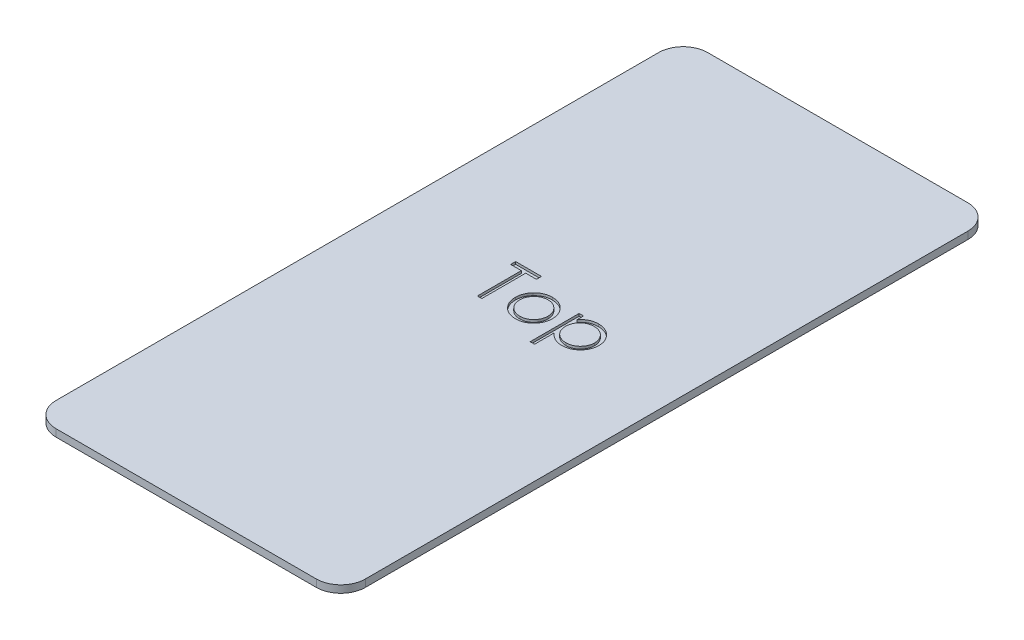
SolidWorks part; units mm, degrees
ref_plane "Front Plane" through (0, 0, 0) normal (0, 0, 1) x (1, 0, 0)
ref_plane "Top Plane" through (0, 0, 0) normal (0, 1, 0) x (1, 0, 0)
ref_plane "Right Plane" through (0, 0, 0) normal (1, 0, 0) x (0, 0, -1)
sketch "Sketch1" plane through (0, 0, 0) normal (0, 1, 0) x (1, 0, 0)
  line L1 (-63.105, -132.955) -> (63.105, -132.955)
  line L2 (-63.105, -132.955) -> (-63.105, 132.955)
  line L3 (-63.105, 132.955) -> (63.105, 132.955)
  line L4 (63.105, -132.955) -> (63.105, 132.955)
  line L5 (-63.105, -132.955) -> (63.105, 132.955) construction
  line L6 (-63.105, 132.955) -> (63.105, -132.955) construction
  point P0 (0, 0)
  dimension "D1" = 265.91
  dimension "D2" = 126.21
extrude "Boss-Extrude1" add sketch "Sketch1" along normal blind 3
sketch "Sketch2" plane through (0, 3, 0) normal (0, 1, 0) x (1, 0, 0)
  text T0 "Top" font "Century Gothic" height 20
  point P1 (0, 0)
extrude "Cut-Extrude1" cut sketch "Sketch2" against normal blind 1
fillet "Fillet1" radius 10 4 edges at (-63.105, 1.5, 132.955) (-63.105, 1.5, -132.955) (63.105, 1.5, -132.955) (63.105, 1.5, 132.955)
